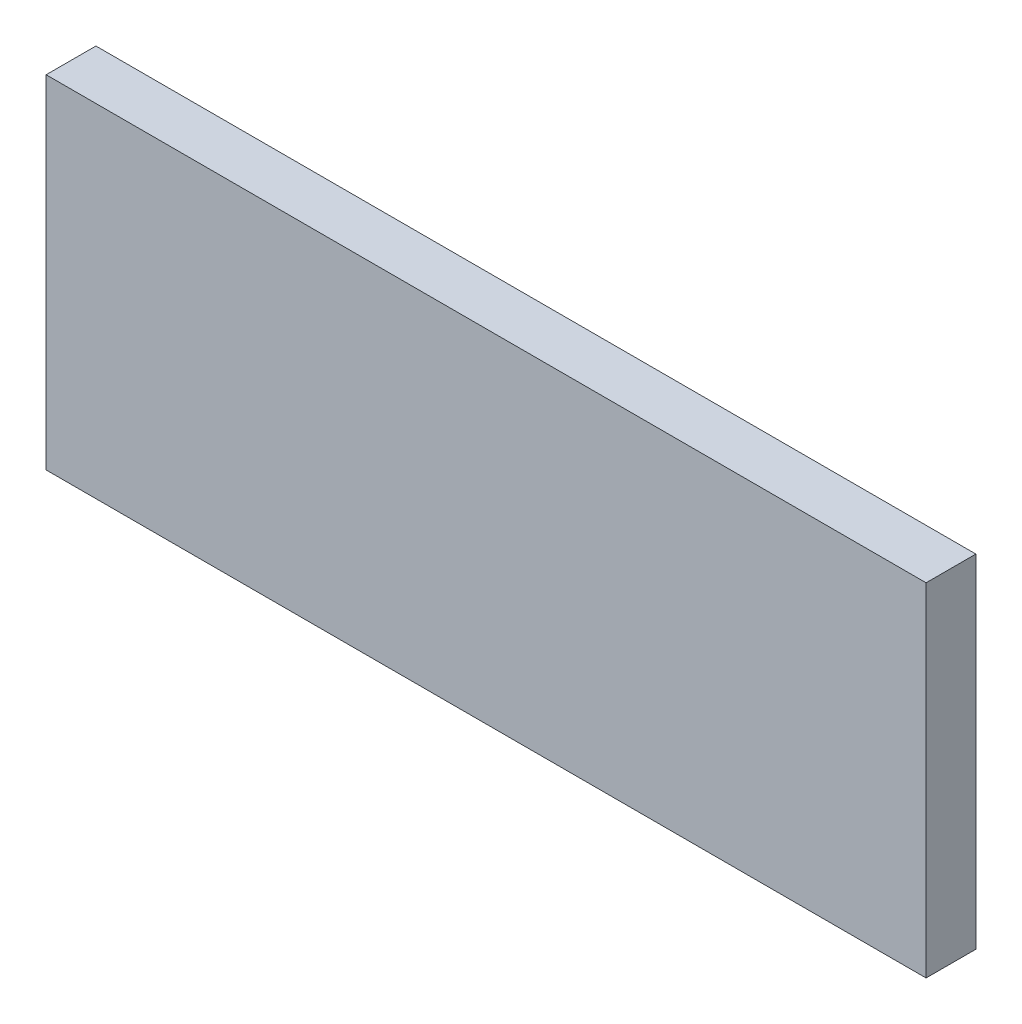
SolidWorks part; units mm, degrees
material "ABS"
ref_plane "前视基准面" through (0, 0, 0) normal (0, 0, 1) x (1, 0, 0)
ref_plane "上视基准面" through (0, 0, 0) normal (0, 1, 0) x (1, 0, 0)
ref_plane "右视基准面" through (0, 0, 0) normal (1, 0, 0) x (0, 0, -1)
other "Configuration Table"
sketch "草图1" plane through (0, 0, 0) normal (0, 0, 1) x (1, 0, 0)
  line L1 (0, 0) -> (14.14, 0)
  line L2 (0, 0) -> (0, -5.5)
  line L3 (0, -5.5) -> (14.14, -5.5)
  line L4 (14.14, 0) -> (14.14, -5.5)
  dimension "D1" = 14.14
  dimension "D2" = 5.5
extrude "凸台-拉伸1" add sketch "草图1" along normal blind 0.8
